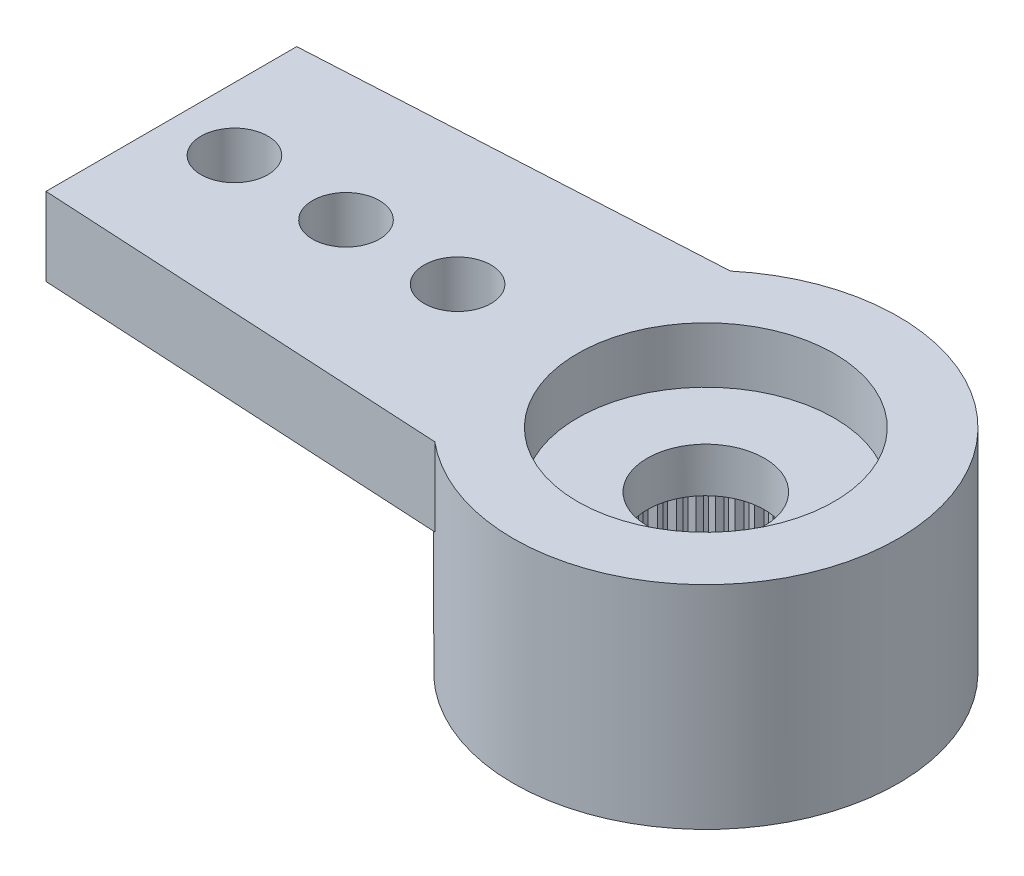
SolidWorks part; units mm, degrees
material "PVC Rígido"
ref_plane "Plano frontal" through (0, 0, 0) normal (0, 0, 1) x (1, 0, 0)
ref_plane "Plano superior" through (0, 0, 0) normal (0, 1, 0) x (1, 0, 0)
ref_plane "Plano direito" through (0, 0, 0) normal (1, 0, 0) x (0, 0, -1)
sketch "Esboço1" plane through (0, 0, 0) normal (0, 1, 0) x (1, 0, 0)
  line L0 (0, 0) -> (-14.05, 0) construction
  line L1 (-14.1591, 1.997) -> (-2.2091, 2.65)
  line L2 (-2.2091, -2.65) -> (-14.1591, -1.997)
  arc A0 (-2.2091, -2.65) -> (-2.2091, 2.65) centre (0, 0) ccw
  arc A1 (-14.1591, 1.997) -> (-14.1591, -1.997) centre (-14.05, 0) ccw
  dimension "D1" = 6.9
  dimension "D2" = 4
  dimension "D3" = 19.5
  dimension "D4" = 5.3
extrude "Ressalto-extrusão1" add sketch "Esboço1" against normal blind 1.4
sketch "Esboço2" plane through (0, -1.4, 0) normal (0, -1, 0) x (1, 0, 0)
  arc A0 (-2.2091, -2.65) -> (-2.2091, 2.65) centre (0, 0) ccw construction
  circle A1 centre (0, 0) radius 3.45
extrude "Ressalto-extrusão2" add sketch "Esboço2" along normal offset from surface (2.4 mm away) 3.8 up to face at (-7.242, 0, 0)
hole_wizard "Furo4" positions "Esboço9" profile "Esboço10" legacy end condition through all
sketch "Esboço9" plane through (0, 0, 0) normal (0, 1, 0) x (1, 0, 0)
  line L1 (-14.45, 0) -> (0, 0) construction
  arc A2 (-14.1591, 1.997) -> (-14.1591, -1.997) centre (-14.05, 0) ccw construction
  point P0 (-14.45, 0)
  point P19 (-16.05, 0)
  dimension "D1" = 1.6
sketch "Esboço10" plane through (-14.45, 0, 0) normal (1, 0, 0) x (0, 0, 1)
  line L0 (0, 0) -> (0, 3.8)
  line L1 (0, 3.8) -> (0.6, 3.8)
  line L2 (0.6, 3.8) -> (0.6, 0)
  line L3 (0.6, 0) -> (0, 0)
  line L4 (0, 110) -> (0, -10) construction
  dimension "Diameter" = 1.2
  dimension "Depth" = 3.8
pattern_linear "Padrão linear1" count 6 spacing 2 along (1, 0, 0) of "Furo4"
hole_wizard "Furo1" positions "Esboço3" profile "Esboço4" legacy
sketch "Esboço3" plane through (0, -3.8, 0) normal (0, -1, 0) x (-1, 0, 0)
  point P0 (0, 0)
sketch "Esboço4" plane through (0, -3.8, 0) normal (1, 0, 0) x (0, 0, -1)
  line L0 (0, 0) -> (0, 2)
  line L1 (0, 2) -> (2.475, 2)
  line L2 (2.475, 2) -> (2.475, 0)
  line L3 (2.475, 0) -> (0, 0)
  line L4 (0, 110) -> (0, -10) construction
  dimension "Diameter" = 4.95
  dimension "Depth" = 2
hole_wizard "Furo2" positions "Esboço5" profile "Esboço6" legacy
sketch "Esboço5" plane through (0, 0, 0) normal (0, 1, 0) x (1, 0, 0)
  point P0 (0, 0)
sketch "Esboço6" plane through (0, 0, 0) normal (1, 0, 0) x (0, 0, 1)
  line L0 (0, 0) -> (0, 1)
  line L1 (0, 1) -> (2.3, 1)
  line L2 (2.3, 1) -> (2.3, 0)
  line L3 (2.3, 0) -> (0, 0)
  line L4 (0, 110) -> (0, -10) construction
  dimension "Diameter" = 4.6
  dimension "Depth" = 1
hole_wizard "Furo3" positions "Esboço7" profile "Esboço8" legacy end condition through all
sketch "Esboço7" plane through (0, 0, 0) normal (0, 1, 0) x (1, 0, 0)
  point P0 (0, 0)
sketch "Esboço8" plane through (0, 0, 0) normal (1, 0, 0) x (0, 0, 1)
  line L0 (0, 0) -> (0, 3.8)
  line L1 (0, 3.8) -> (1.05, 3.8)
  line L2 (1.05, 3.8) -> (1.05, 0)
  line L3 (1.05, 0) -> (0, 0)
  line L4 (0, 110) -> (0, -10) construction
  dimension "Diameter" = 2.1
  dimension "Depth" = 3.8
sketch "Esboço11" plane through (0, -3.8, 0) normal (0, -1, 0) x (1, 0, 0)
  line L0 (-0.0981, 2.4731) -> (0, 2.375)
  line L1 (0, 2.375) -> (0.0981, 2.4731)
  line L2 (0, 0) -> (0, 2.475) construction
  circle A0 centre (0, 0) radius 2.375 construction
  circle A1 centre (0, 0) radius 2.475
  arc A2 (0.0981, 2.4731) -> (-0.0981, 2.4731) centre (0, 0) ccw
  dimension "D3" = 4.75
  dimension "D2" = 0.1
  dimension "D1" = 0
extrude "Ressalto-extrusão3" add sketch "Esboço11" against normal up to surface (2 mm away) up to face at (0, -1.8, 1.05)
pattern_circular "PadrãoCircular1" count 60 over 360 about axis through (0, 0, 0) along (0, 1, 0) of "Ressalto-extrusão3"
sketch "Sketch1" plane through (0, 0, 0) normal (0, 1, 0) x (1, 0, 0)
  line L1 (-17.7516, 5.1171) -> (-9.5807, 5.1171)
  line L2 (-17.7516, 5.1171) -> (-17.7516, -4.5187)
  line L3 (-17.7516, -4.5187) -> (-9.5807, -4.5187)
  line L4 (-9.5807, 5.1171) -> (-9.5807, -4.5187)
extrude "Cut-Extrude1" cut sketch "Sketch1" against normal blind 10
